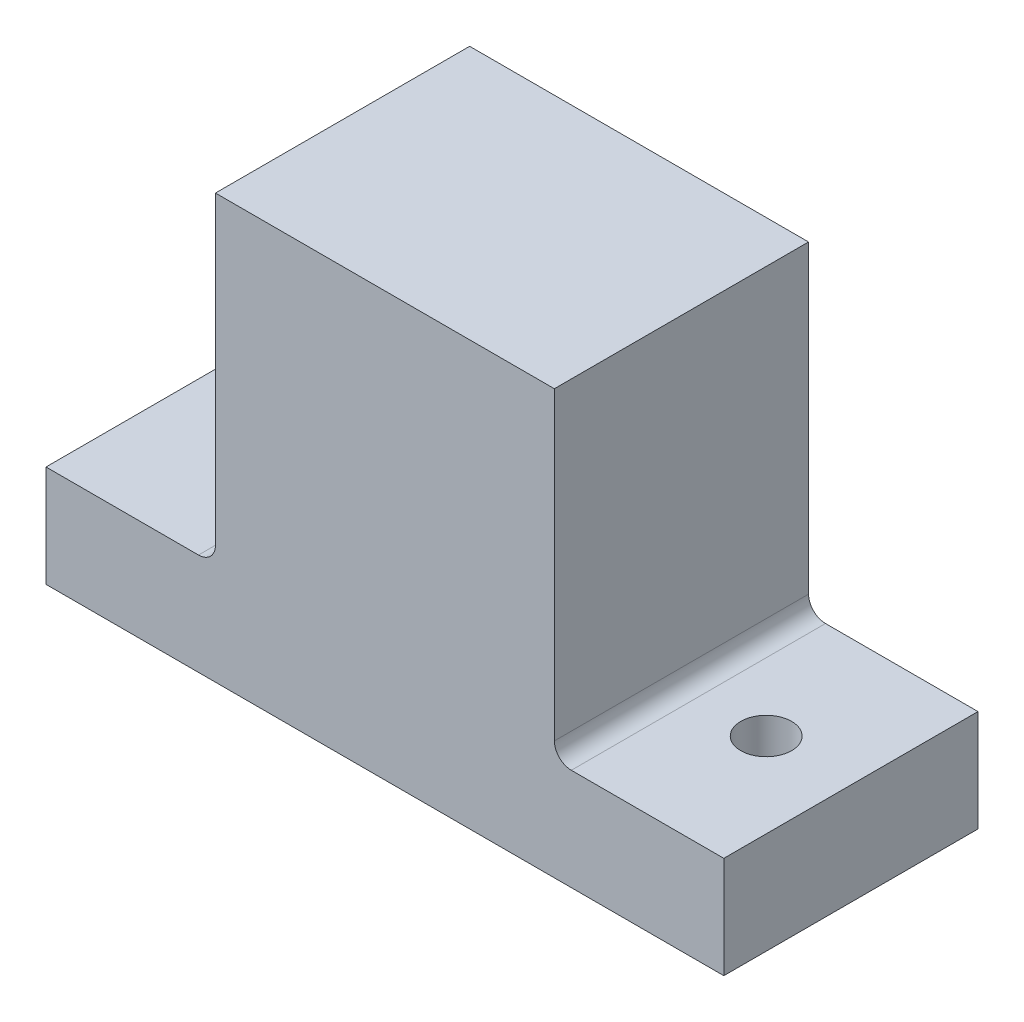
SolidWorks part; units mm, degrees
material "POM 乙缩醛共聚物"
ref_plane "前视基准面" through (0, 0, 0) normal (0, 0, 1) x (1, 0, 0)
ref_plane "上视基准面" through (0, 0, 0) normal (0, 1, 0) x (1, 0, 0)
ref_plane "右视基准面" through (0, 0, 0) normal (1, 0, 0) x (0, 0, -1)
sketch "草图1" plane through (0, 0, 0) normal (0, 0, 1) x (1, 0, 0)
  line L0 (0, 0) -> (0, 25) construction
  line L1 (20, 0) -> (-20, 0)
  line L2 (-20, 0) -> (-20, 6)
  line L3 (20, 0) -> (20, 6)
  line L4 (-20, 6) -> (-10, 6)
  line L5 (20, 6) -> (10, 6)
  line L6 (-10, 6) -> (-10, 25)
  line L7 (10, 6) -> (10, 25)
  line L8 (-10, 25) -> (10, 25)
  point P12 (0, 25)
  dimension "D1" = 40
  dimension "D2" = 20
  dimension "D3" = 25
  dimension "D4" = 6
extrude "凸台-拉伸1" add sketch "草图1" along normal blind 15
sketch "草图2" plane through (0, 6, 0) normal (0, 1, 0) x (1, 0, 0)
  line L0 (-20, -7.5) -> (20, -7.5) construction
  line L1 (-20, -15) -> (-20, 0) construction
  line L2 (20, -15) -> (20, 0) construction
  line L3 (0, 0) -> (0, -7.5) construction
  circle A0 centre (-15, -7.5) radius 1.5
  circle A1 centre (15, -7.5) radius 1.5
  dimension "D1" = 3
  dimension "D2" = 5
extrude "切除-拉伸1" cut sketch "草图2" against normal through all
fillet "圆角1" radius 1 2 edges at (10, 6, 7.5) (-10, 6, 7.5)
